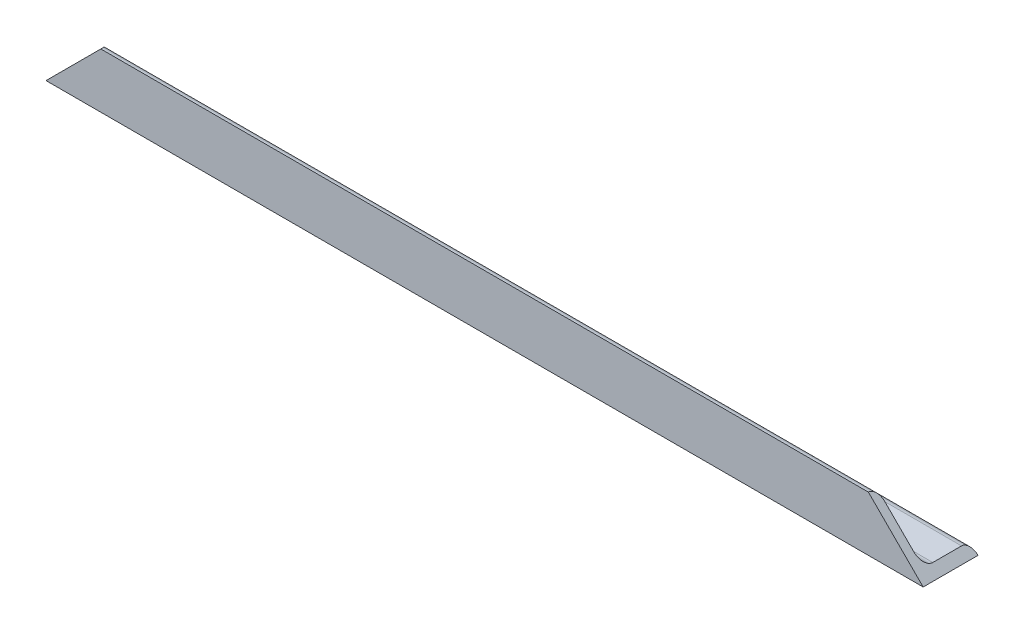
SolidWorks part; units mm, degrees
ref_plane "Front Plane" through (0, 0, 0) normal (0, 0, 1) x (1, 0, 0)
ref_plane "Top Plane" through (0, 0, 0) normal (0, 1, 0) x (1, 0, 0)
ref_plane "Right Plane" through (0, 0, 0) normal (1, 0, 0) x (0, 0, -1)
sketch "Sketch1" plane through (0, 0, 0) normal (0, 1, 0) x (1, 0, 0)
  line L0 (0, 0) -> (320, 0)
  dimension "D1" = 320
other "L angle (equal) 20X20X3(1)"
ref_plane "Plane1" through (0, 0, 0) normal (1, 0, 0) x (0, 0, -1)
sketch "Sketch16" plane through (0, 0, 0) normal (1, 0, 0) x (0, 0, -1)
  line L0 (0, 20) -> (0, 0)
  line L2 (3, 17) -> (3, 6.5)
  line L3 (6.5, 3) -> (17, 3)
  line L5 (20, 0) -> (0, 0)
  arc A0 (3, 17) -> (0, 20) centre (0, 17) ccw
  arc A1 (20, 0) -> (17, 3) centre (17, 0) ccw
  arc A2 (6.5, 3) -> (3, 6.5) centre (6.5, 6.5) cw
  point P8 (0, 10)
  point P9 (10, 0)
  point P10 (0, 0)
  dimension "Radius_2" = 3
  dimension "Radius_1" = 3.5
  dimension "V_leg" = 20
  dimension "H_leg" = 20
  dimension "thickness" = 3
sketch "Sketch14" plane through (0, 0, 0) normal (0, 0, 1) x (1, 0, 0)
  line L0 (320, 0) -> (320, 20)
  line L1 (0, 20) -> (0, 0)
  line L2 (20, 20) -> (0, 0)
  line L3 (300, 20) -> (320, 0)
  line L4 (0, 20) -> (0, 0)
  line L5 (0, 0) -> (320, 0)
  line L6 (320, 0) -> (320, 20)
  line L7 (320, 20) -> (0, 20)
  line L8 (0, 20) -> (0, 0) construction
  line L10 (320, 0) -> (320, 20) construction
  line L11 (320, 20) -> (300, 20)
  line L12 (20, 20) -> (0, 20)
  dimension "D2" = 20
  dimension "D3" = 20
  dimension "D1" = 0
extrude "Cut-Extrude1" cut sketch "Sketch14" against normal through all
